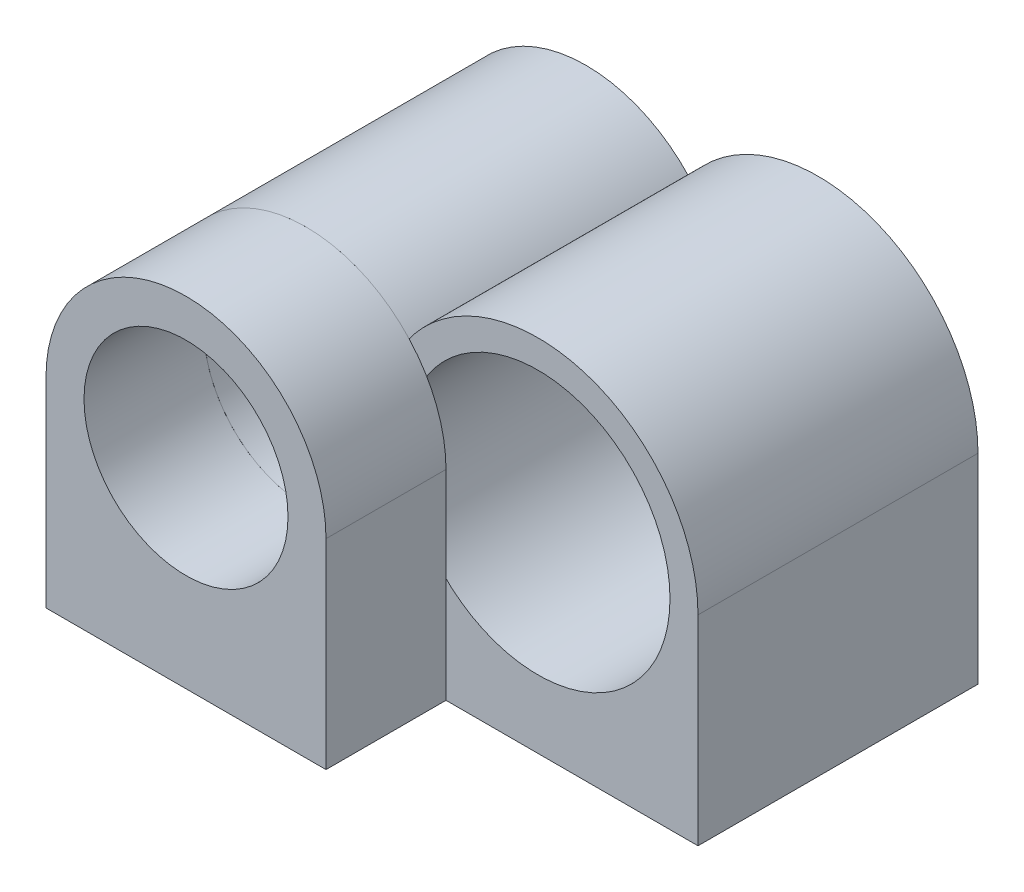
SolidWorks part; units mm, degrees
ref_plane "Front Plane" through (0, 0, 0) normal (0, 0, 1) x (1, 0, 0)
ref_plane "Top Plane" through (0, 0, 0) normal (0, 1, 0) x (1, 0, 0)
ref_plane "Right Plane" through (0, 0, 0) normal (1, 0, 0) x (0, 0, -1)
sketch "Sketch1" plane through (0, 0, 0) normal (0, 0, 1) x (1, 0, 0)
  line L0 (-4, 0) -> (-4, -5)
  line L1 (-4, -5) -> (4, -5)
  line L2 (4, -5) -> (4, 0)
  circle A0 centre (0, 0) radius 3.3
  arc A1 (4, 0) -> (-4, 0) centre (0, 0) ccw
  dimension "D1" = 6.6
  dimension "D2" = 8
  dimension "D3" = 5
extrude "Boss-Extrude1" add sketch "Sketch1" along normal blind 7
sketch "Sketch2" plane through (0, 0, 7) normal (0, 0, 1) x (1, 0, 0)
  line L0 (-9.3, 0) -> (-9.3, -5)
  line L1 (-9.3, -5) -> (-4, -5)
  line L3 (-2.3, 0) -> (-2.3, -5)
  line L4 (-4, -5) -> (4, -5) construction
  line L5 (-2.3, -5) -> (-4, -5)
  circle A0 centre (-5.8, 0) radius 2.55
  arc A1 (-2.3, 0) -> (-9.3, 0) centre (-5.8, 0) ccw
  dimension "D1" = 5.1
  dimension "D3" = 7
  dimension "D2" = 5.8
extrude "Boss-Extrude4" add sketch "Sketch2" along normal blind 3 separate body contours A1 L0 L1 L5 L3 | A0
sketch "Sketch6" plane through (0, 0, 7) normal (0, 0, -1) x (-1, 0, 0)
  line L0 (4, 0) -> (4, -5) construction
  line L1 (4, 0) -> (4, -5)
  line L3 (2.3, 0) -> (2.3, -5)
  line L4 (2.3, -5) -> (9.3, -5)
  line L5 (9.3, -5) -> (9.3, 0)
  line L6 (2.3, 0) -> (2.3, -5)
  line L7 (2.3, -5) -> (9.3, -5)
  line L8 (9.3, -5) -> (9.3, 0)
  circle A0 centre (5.8, 0) radius 2.55 construction
  arc A1 (9.3, 0) -> (2.3, 0) centre (5.8, 0) ccw
  arc A2 (9.3, 0) -> (2.3, 0) centre (5.8, 0) ccw
  circle A3 centre (5.8, 0) radius 2.55
  arc A5 (4, 0) -> (-4, 0) centre (0, 0) ccw construction
  arc A6 (4, 0) -> (-4, 0) centre (0, 0) ccw
  line M6 (2.3, -5) -> (9.3, -5)
  line M7 (9.3, -5) -> (9.3, 0)
  arc M8 (9.3, 0) -> (2.3, 0) centre (5.8, 0) ccw
  dimension "D1" = 0
extrude "Boss-Extrude10" add sketch "Sketch6" along normal blind 7 separate body contours A6 A3 L1 M6 M7 M8
